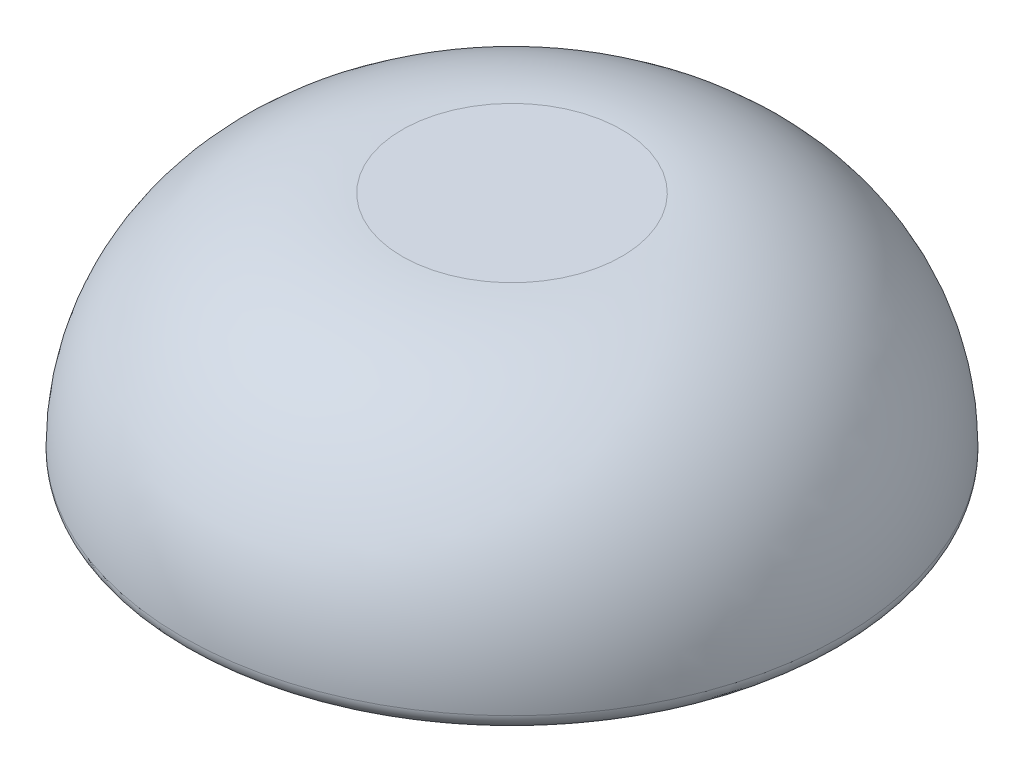
SolidWorks part; units mm, degrees
ref_plane "Front Plane" through (0, 0, 0) normal (0, 0, 1) x (1, 0, 0)
ref_plane "Top Plane" through (0, 0, 0) normal (0, 1, 0) x (1, 0, 0)
ref_plane "Right Plane" through (0, 0, 0) normal (1, 0, 0) x (0, 0, -1)
sketch "Sketch1" plane through (0, 0, 0) normal (0, 0, 1) x (1, 0, 0)
  line L0 (0, 30) -> (10, 30)
  line L1 (0, -16.5) -> (0, 16.5) construction
  line L2 (16.5, 0) -> (-16.5, 0) construction
  line L3 (6, 22) -> (6, 0)
  line L4 (6, 0) -> (3.8, 0)
  line L5 (3.8, 0) -> (3.8, 25)
  line L6 (3.8, 25) -> (0, 25)
  line L7 (0, 33.3867) -> (0, -3.037) construction
  line L8 (0, 30) -> (0, 25)
  arc A0 (10, 30) -> (30, 10) centre (10, 10) cw
  arc A1 (30, 10) -> (27, 10) centre (28.5, 10) cw
  arc A2 (27, 10) -> (11.4164, 26.9409) centre (10, 10) ccw
  arc A3 (11.4164, 26.9409) -> (6, 22) centre (10.9998, 21.9583) ccw
  dimension "D3" = 3
  dimension "D1" = 30
  dimension "D2" = 10
  dimension "D4" = 6
  dimension "D5" = 3.8
  dimension "D6" = 25
  dimension "D7" = 10
revolve "Revolve1" add sketch "Sketch1" angle 360 about L7
sketch "Sketch3" plane through (0, 0, 0) normal (0, 0, 1) x (1, 0, 0)
  line L0 (0, -16.5) -> (0, 16.5) construction
  line L1 (-1.5, 22.5) -> (1.5, 22.5)
  line L2 (-1.5, 22.5) -> (-1.5, 14.5)
  line L3 (-1.5, 14.5) -> (1.5, 14.5)
  line L4 (1.5, 22.5) -> (1.5, 14.5)
  line L5 (-1.5, 22.5) -> (1.5, 14.5) construction
  line L6 (-1.5, 14.5) -> (1.5, 22.5) construction
  line L7 (10, 30) -> (-10, 30) construction
  point P0 (0, 18.5)
  dimension "D1" = 3
  dimension "D2" = 8
  dimension "D3" = 7.5
extrude "Cut-Extrude1" cut sketch "Sketch3" against normal blind 10
sketch "Sketch4" plane through (0, 0, 0) normal (0, 0, 1) x (1, 0, 0)
  line L0 (0, 31.0799) -> (0, -1.8014) construction
  line L1 (0, -16.5) -> (0, 16.5) construction
pattern_circular "CirPattern1" count 6 over 360 about axis through (0, 0, 0) along (0, 1, 0) of "Cut-Extrude1"
chamfer "Chamfer1" distance 0.5 angle 45 1 edges at (0, 0, 3.8)
